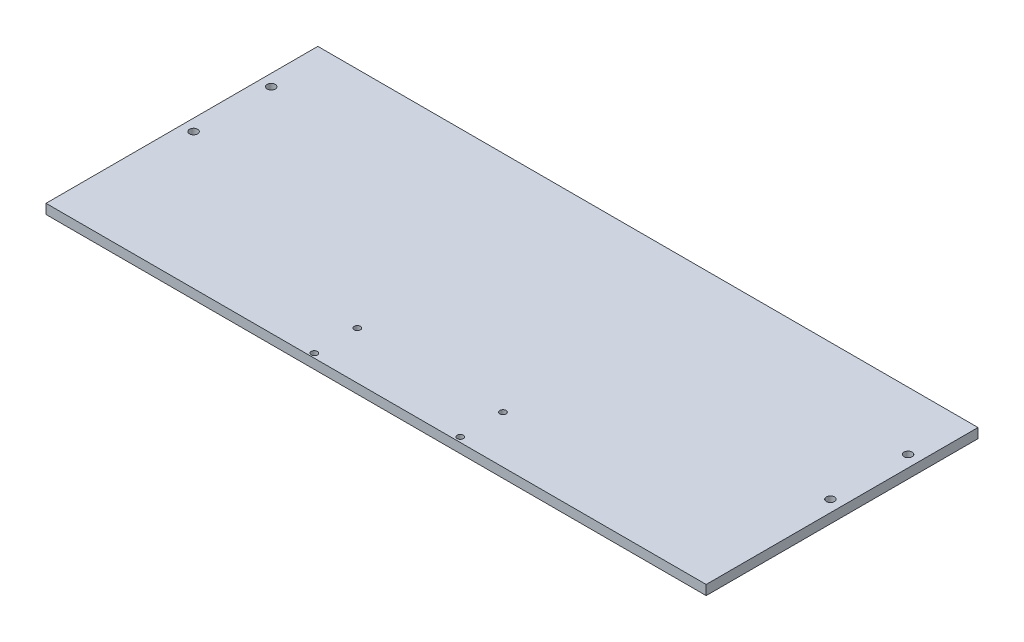
SolidWorks part; units mm, degrees
ref_plane "前视基准面" through (0, 0, 0) normal (0, 0, 1) x (1, 0, 0)
ref_plane "上视基准面" through (0, 0, 0) normal (0, 1, 0) x (1, 0, 0)
ref_plane "右视基准面" through (0, 0, 0) normal (1, 0, 0) x (0, 0, -1)
other "Configuration Table"
sketch "草图1" plane through (0, 0, 0) normal (0, 1, 0) x (1, 0, 0)
  line L0 (-34.0557, -70) -> (-34.0557, -65.4967) construction
  line L1 (-170, -70) -> (170, -70)
  line L2 (-170, -70) -> (-170, 70)
  line L3 (-170, 70) -> (170, 70)
  line L4 (170, -70) -> (170, 70)
  line L5 (-170, -70) -> (170, 70) construction
  line L6 (-170, 70) -> (170, -70) construction
  circle A0 centre (164, 40) radius 2.1
  circle A1 centre (164, 0) radius 2.1
  circle A2 centre (-164, 40) radius 2.1
  circle A3 centre (-164, 0) radius 2.1
  circle A4 centre (-34.1557, -45.5) radius 1.6
  circle A6 centre (-34.0557, -67.7483) radius 1.6
  circle A7 centre (40.8443, -67.5) radius 1.6
  circle A8 centre (40.8443, -45.5) radius 1.6
  point P0 (0, 0)
  dimension "D3" = 4.2
  dimension "D4" = 3.2
  dimension "D1" = 140
  dimension "D2" = 340
extrude "凸台-拉伸1" add sketch "草图1" along normal blind 5
